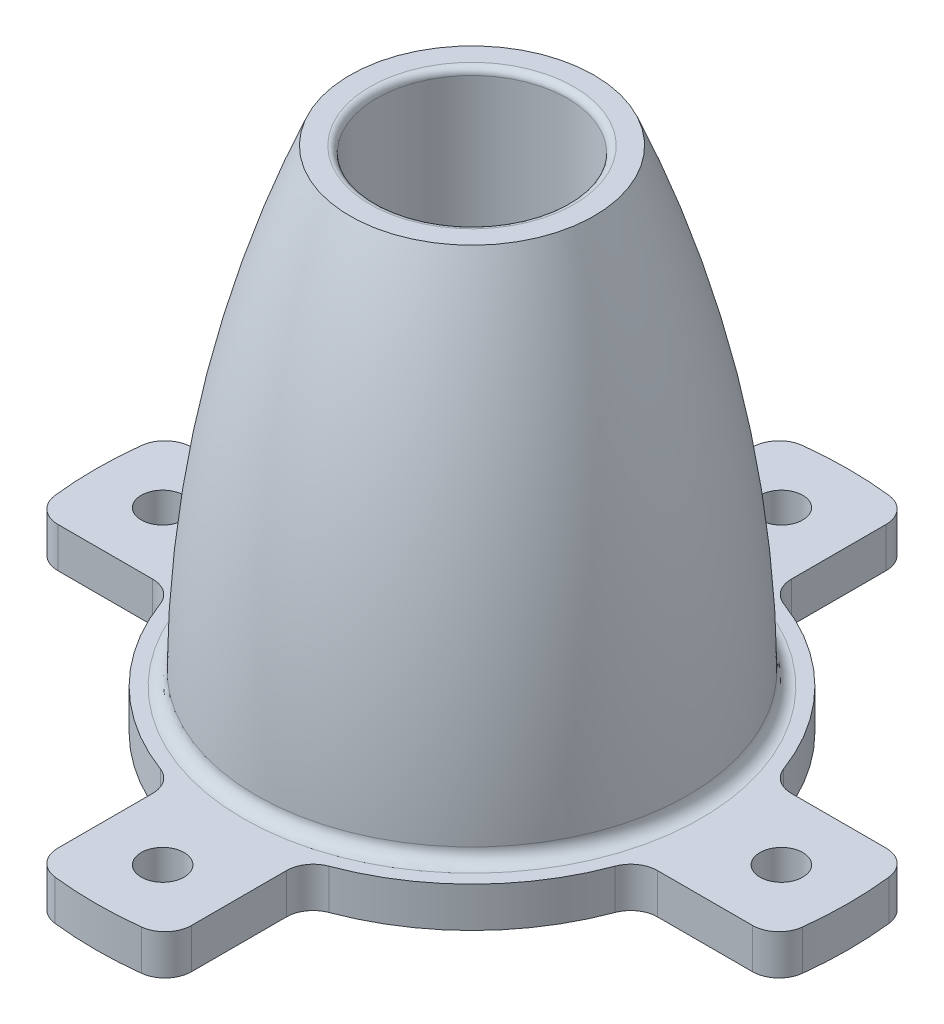
SolidWorks part; units mm, degrees
ref_plane "Front Plane" through (0, 0, 0) normal (0, 0, 1) x (1, 0, 0)
ref_plane "Top Plane" through (0, 0, 0) normal (0, 1, 0) x (1, 0, 0)
ref_plane "Right Plane" through (0, 0, 0) normal (1, 0, 0) x (0, 0, -1)
sketch "Sketch1" plane through (0, 0, 0) normal (0, 0, 1) x (1, 0, 0)
  line L1 (-28.125, 0) -> (-28.125, 3)
  line L2 (-28.125, 3) -> (-16.125, 3)
  line L3 (0, 0) -> (0, 31.5) construction
  line L5 (-16.125, 3) -> (-16.125, -21.5795) construction
  line L6 (-7.125, 38) -> (-7.125, 0)
  line L7 (-7.125, 0) -> (-28.125, 0)
  line L8 (-9.125, 38) -> (-7.125, 38)
  arc A0 (-16.125, 3) -> (-9.125, 38) centre (74.875, 3) cw
  dimension "D1" = 7.125
  dimension "D2" = 2
  dimension "D3" = 21
  dimension "D4" = 3
  dimension "D5" = 12
  dimension "D6" = 38
revolve "Revolve1" add sketch "Sketch1" angle 360 about L3
sketch "Sketch2" plane through (0, 0, 0) normal (0, -1, 0) x (1, 0, 0)
  line L1 (0, 12.8172) -> (-11.1, 6.4086)
  line L2 (-11.1, 6.4086) -> (-11.1, -6.4086)
  line L3 (-11.1, -6.4086) -> (0, -12.8172)
  line L4 (0, -12.8172) -> (11.1, -6.4086)
  line L5 (11.1, -6.4086) -> (11.1, 6.4086)
  line L6 (11.1, 6.4086) -> (0, 12.8172)
  circle A0 centre (0, 0) radius 11.1 construction
  dimension "D1" = 22.2
extrude "Cut-Extrude1" cut sketch "Sketch2" against normal blind 25
sketch "Sketch3" plane through (0, 3, 0) normal (0, 1, 0) x (1, 0, 0)
  line L0 (28.125, 0) -> (-28.125, 0) construction
  line L1 (0, 28.125) -> (0, -28.125) construction
  line L2 (5, -15.3302) -> (5, -27.677)
  line L3 (-5, -15.3302) -> (-5, -27.677)
  line L4 (-15.3302, 5) -> (-27.677, 5)
  line L5 (-15.3302, -5) -> (-27.677, -5)
  line L6 (5, 15.3302) -> (5, 27.677)
  line L7 (-5, 15.3302) -> (-5, 27.677)
  line L8 (15.3302, -5) -> (27.677, -5)
  line L9 (15.3302, 5) -> (27.677, 5)
  circle A0 centre (0, 0) radius 28.125 construction
  circle A1 centre (0, 0) radius 16.125
  circle A2 centre (0, 0) radius 28.125
  circle A3 centre (0, 0) radius 16.125 construction
  circle A4 centre (0, 0) radius 18.125
  point P8 (0, 0)
  point P14 (0, 0)
  point P34 (0.4613, -0.5934)
  point P36 (0, 0)
  dimension "D3" = 4
  dimension "D4" = 2
  dimension "D1" = 5
  dimension "D2" = 5
  dimension "D5" = 5
extrude "Cut-Extrude2" cut sketch "Sketch3" against normal blind 22
sketch "Sketch4" plane through (0, 3, 0) normal (0, 1, 0) x (1, 0, 0)
  circle A2 centre (23.125, 0) radius 1.6
  circle A6 centre (0, 0) radius 23.125 construction
  arc A7 (27.677, -5) -> (27.677, 5) centre (0, 0) ccw construction
  circle A8 centre (0, -23.125) radius 1.6
  circle A9 centre (-23.125, 0) radius 1.6
  circle A10 centre (0, 23.125) radius 1.6
  point P17 (0, 0)
  dimension "D1" = 5
  dimension "D2" = 3.2
  dimension "D3" = 4
extrude "Cut-Extrude3" cut sketch "Sketch4" against normal through all
fillet "Fillet3" radius 0.5 8 edges at (0, 38, -7.125) (0, 25, -7.125) (-11.1, 25, 0) (-5.55, 25, -9.6129) (5.55, 25, -9.6129) (11.1, 25, 0) (5.55, 25, 9.6129) (-5.55, 25, 9.6129)
fillet "Fillet6" radius 2 16 edges at (27.677, 1.5, -5) (27.677, 1.5, 5) (5, 1.5, 27.677) (-5, 1.5, 27.677) (-27.677, 1.5, 5) (-27.677, 1.5, -5) (5, 1.5, -27.677) (-5, 1.5, -27.677) (-17.4217, 1.5, -5) (-5, 1.5, -17.4217) (5, 1.5, -17.4217) (17.4217, 1.5, -5) (17.4217, 1.5, 5) (5, 1.5, 17.4217) (-5, 1.5, 17.4217) (-17.4217, 1.5, 5)
fillet "Fillet7" radius 1 1 edges at (0, 3, -16.125)
